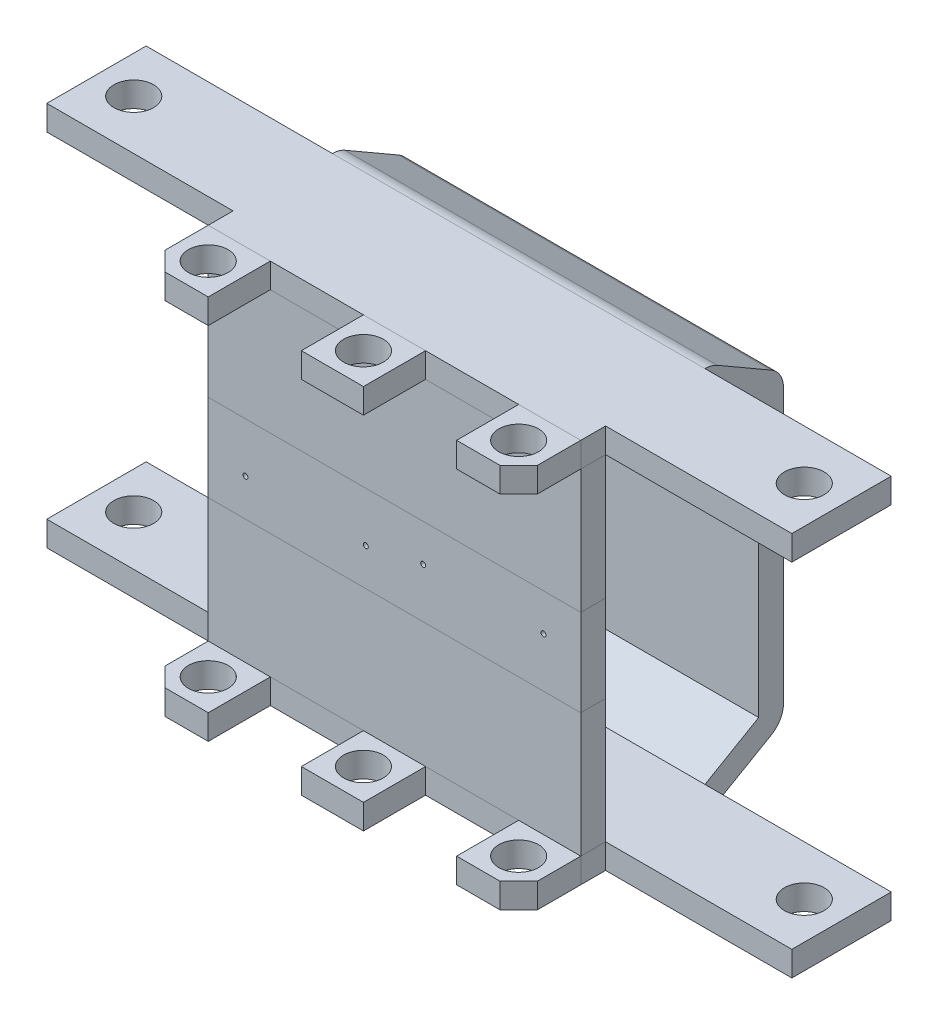
SolidWorks part; units mm, degrees
material "Mahogany"
ref_plane "Front Plane" through (0, 0, 0) normal (0, 0, 1) x (1, 0, 0)
ref_plane "Top Plane" through (0, 0, 0) normal (0, 1, 0) x (1, 0, 0)
ref_plane "Right Plane" through (0, 0, 0) normal (1, 0, 0) x (0, 0, -1)
sketch "Sketch1" plane through (0, 0, 0) normal (0, 0, 1) x (1, 0, 0)
  line L1 (0, 0) -> (-300, 0)
  line L2 (0, 0) -> (0, 200)
  line L3 (0, 200) -> (-300, 200)
  line L4 (-300, 0) -> (-300, 200)
  dimension "D1" = 300
  dimension "D2" = 200
extrude "Boss-Extrude1" add sketch "Sketch1" along normal blind 20
sketch "Sketch2" plane through (0, 0, 20) normal (0, 0, 1) x (1, 0, 0)
  line L0 (0, 200) -> (-300, 200) construction
  line L1 (-300, 200) -> (-300, 0) construction
  circle A0 centre (-270, 160) radius 2
  circle A1 centre (-173.0937, 160) radius 2
  dimension "D2" = 40
  dimension "D1" = 96.9063
  dimension "D3" = 40
  dimension "D4" = 30
extrude "Cut-Extrude1" cut sketch "Sketch2" against normal blind 20
sketch "Sketch3" plane through (0, 0, 0) normal (0, 0, -1) x (-1, 0, 0)
  line L0 (0, 0) -> (0, 200) construction
  line L1 (300, 0) -> (0, 0)
  line L2 (300, 0) -> (300, 130)
  line L3 (300, 130) -> (0, 130)
  line L4 (0, 0) -> (0, 130)
  dimension "D1" = 130
extrude "Cut-Extrude2" cut sketch "Sketch3" against normal blind 20
sketch "Sketch4" plane through (0, 0, 0) normal (0, 0, -1) x (-1, 0, 0)
  line L0 (0, 130) -> (0, 200) construction
  line L1 (0, 200) -> (300, 200) construction
  line L2 (300, 130) -> (0, 130) construction
  circle A0 centre (30, 170) radius 2
  circle A1 centre (126.9063, 170) radius 2
  dimension "D1" = 30
  dimension "D2" = 30
  dimension "D3" = 40
  dimension "D4" = 96.9063
extrude "Cut-Extrude3" cut sketch "Sketch4" against normal blind 20
sketch "Sketch5" plane through (0, 200, 0) normal (0, 1, 0) x (1, 0, 0)
  line L1 (0, -20) -> (-300, -20)
  line L2 (0, -20) -> (0, 0)
  line L3 (0, 0) -> (-300, 0)
  line L4 (-300, -20) -> (-300, 0)
extrude "Boss-Extrude2" add sketch "Sketch5" along normal blind 100 separate body
sketch "Sketch6" plane through (0, 130, 0) normal (0, -1, 0) x (1, 0, 0)
  line L1 (-300, 20) -> (0, 20)
  line L2 (-300, 20) -> (-300, 0)
  line L3 (-300, 0) -> (0, 0)
  line L4 (0, 20) -> (0, 0)
extrude "Boss-Extrude3" add sketch "Sketch6" along normal blind 100 separate body
sketch "Sketch9" plane through (0, 30, 0) normal (0, -1, 0) x (1, 0, 0)
  line L1 (-300, 20) -> (0, 20)
  line L2 (-300, 20) -> (-300, -80)
  line L3 (-300, -80) -> (0, -80)
  line L4 (0, 20) -> (0, -80)
  dimension "D1" = 100
extrude "Boss-Extrude6" add sketch "Sketch9" along normal blind 20 separate body
sketch "Sketch10" plane through (0, 300, 0) normal (0, 1, 0) x (1, 0, 0)
  line L1 (0, -20) -> (-300, -20)
  line L2 (0, -20) -> (0, 80)
  line L3 (0, 80) -> (-300, 80)
  line L4 (-300, -20) -> (-300, 80)
  dimension "D1" = 100
extrude "Boss-Extrude7" add sketch "Sketch10" along normal blind 20 separate body
sketch "Sketch14" plane through (0, 0, 0) normal (1, 0, 0) x (0, 0, -1)
  line L1 (80, 320) -> (0, 320)
  line L2 (80, 320) -> (80, 300)
  line L3 (80, 300) -> (0, 300)
  line L4 (0, 320) -> (0, 300)
extrude "Boss-Extrude11" add sketch "Sketch14" along normal blind 150 separate body
sketch "Sketch15" plane through (-300, 0, 0) normal (-1, 0, 0) x (0, 0, 1)
  line L1 (-80, 320) -> (0, 320)
  line L2 (-80, 320) -> (-80, 300)
  line L3 (-80, 300) -> (0, 300)
  line L4 (0, 320) -> (0, 300)
extrude "Boss-Extrude12" add sketch "Sketch15" along normal blind 150 separate body
sketch "Sketch16" plane through (-300, 0, 0) normal (-1, 0, 0) x (0, 0, 1)
  line L0 (20, 10) -> (-80, 10) construction
  line L1 (-80, 30) -> (0, 30)
  line L2 (-80, 30) -> (-80, 10)
  line L3 (-80, 10) -> (0, 10)
  line L4 (0, 30) -> (0, 10)
extrude "Boss-Extrude13" add sketch "Sketch16" along normal blind 150 separate body
sketch "Sketch17" plane through (0, 0, 0) normal (1, 0, 0) x (0, 0, -1)
  line L0 (80, 10) -> (-20, 10) construction
  line L1 (80, 30) -> (0, 30)
  line L2 (80, 30) -> (80, 10)
  line L3 (80, 10) -> (0, 10)
  line L4 (0, 30) -> (0, 10)
extrude "Boss-Extrude14" add sketch "Sketch17" along normal blind 150 separate body
sketch "Sketch18" plane through (0, 10, 0) normal (0, -1, 0) x (1, 0, 0)
  line L0 (150, 0) -> (150, -80) construction
  line L1 (150, -80) -> (0, -80) construction
  circle A0 centre (120, -40) radius 16
  dimension "D1" = 30
  dimension "D2" = 40
extrude "Cut-Extrude4" cut sketch "Sketch18" against normal blind 20
sketch "Sketch19" plane through (0, 300, 0) normal (0, -1, 0) x (1, 0, 0)
  line L0 (150, 0) -> (0, 0) construction
  line L1 (150, 0) -> (150, -80) construction
  circle A0 centre (120, -40) radius 16
  dimension "D1" = 40
  dimension "D2" = 30
extrude "Cut-Extrude5" cut sketch "Sketch19" against normal blind 20
sketch "Sketch20" plane through (0, 320, 0) normal (0, 1, 0) x (1, 0, 0)
  line L0 (-450, 0) -> (-300, 0) construction
  line L1 (-450, 0) -> (-450, 80) construction
  circle A0 centre (-420, 40) radius 16
  dimension "D1" = 40
  dimension "D2" = 30
extrude "Cut-Extrude6" cut sketch "Sketch20" against normal blind 20
sketch "Sketch21" plane through (0, 30, 0) normal (0, 1, 0) x (1, 0, 0)
  line L0 (-450, 0) -> (-450, 80) construction
  line L1 (-450, 80) -> (-300, 80) construction
  circle A0 centre (-420, 40) radius 16
  dimension "D1" = 30
  dimension "D2" = 40
extrude "Cut-Extrude7" cut sketch "Sketch21" against normal blind 20
sketch "Sketch22" plane through (0, 0, 20) normal (0, 0, 1) x (1, 0, 0)
  line L0 (-300, 300) -> (0, 300) construction
  line L1 (-300, 320) -> (-250, 320)
  line L2 (-300, 320) -> (-300, 300)
  line L3 (-300, 300) -> (-250, 300)
  line L4 (-250, 320) -> (-250, 300)
  line L5 (-300, 320) -> (0, 320) construction
  line L6 (-175, 320) -> (-125, 320)
  line L7 (-175, 320) -> (-175, 300)
  line L8 (-175, 300) -> (-125, 300)
  line L9 (-125, 320) -> (-125, 300)
  line L11 (0, 320) -> (-50, 320)
  line L12 (0, 320) -> (0, 300)
  line L13 (0, 300) -> (-50, 300)
  line L14 (-50, 320) -> (-50, 300)
  point P18 (-175, 310)
  dimension "D1" = 50
  dimension "D2" = 50
  dimension "D3" = 50
  dimension "D4" = 75
  dimension "D5" = 75
extrude "Boss-Extrude15" add sketch "Sketch22" along normal blind 50 separate body
sketch "Sketch23" plane through (0, 0, 20) normal (0, 0, 1) x (1, 0, 0)
  line L0 (0, 10) -> (-300, 10) construction
  line L1 (-300, 30) -> (-250, 30)
  line L2 (-300, 30) -> (-300, 10)
  line L3 (-300, 10) -> (-250, 10)
  line L4 (-250, 30) -> (-250, 10)
  line L5 (0, 30) -> (-300, 30) construction
  line L6 (-175, 30) -> (-125, 30)
  line L7 (-175, 30) -> (-175, 10)
  line L8 (-175, 10) -> (-125, 10)
  line L9 (-125, 30) -> (-125, 10)
  line L10 (0, 30) -> (-300, 30) construction
  line L11 (0, 10) -> (-50, 10)
  line L12 (0, 10) -> (0, 30)
  line L13 (0, 30) -> (-50, 30)
  line L14 (-50, 10) -> (-50, 30)
  dimension "D1" = 50
  dimension "D2" = 50
  dimension "D3" = 50
  dimension "D4" = 75
extrude "Boss-Extrude16" add sketch "Sketch23" along normal blind 50 separate body
sketch "Sketch24" plane through (0, 10, 0) normal (0, -1, 0) x (1, 0, 0)
  line L1 (-50, 70) -> (-50, 20) construction
  line L2 (-50, 70) -> (0, 70) construction
  line L3 (0, 55) -> (-15, 70)
  line L4 (0, 70) -> (0, 20) construction
  line L5 (0, 70) -> (0, 55)
  line L6 (-15, 70) -> (0, 70)
  circle A0 centre (-25, 45) radius 16
  dimension "D1" = 25
  dimension "D2" = 25
  dimension "D3" = 15
  dimension "D4" = 15
extrude "Cut-Extrude8" cut sketch "Sketch24" against normal blind 20
sketch "Sketch25" plane through (0, 10, 0) normal (0, -1, 0) x (1, 0, 0)
  line L0 (-125, 70) -> (-125, 20) construction
  line L1 (-175, 70) -> (-125, 70) construction
  circle A0 centre (-150, 45) radius 16
  dimension "D1" = 25
  dimension "D2" = 25
extrude "Cut-Extrude9" cut sketch "Sketch25" against normal blind 20
sketch "Sketch26" plane through (0, 10, 0) normal (0, -1, 0) x (1, 0, 0)
  line L0 (-300, 70) -> (-250, 70) construction
  line L1 (-300, 70) -> (-300, 20) construction
  line L2 (-300, 55) -> (-285, 70)
  line L3 (-285, 70) -> (-300, 70)
  line L4 (-300, 70) -> (-300, 55)
  circle A0 centre (-275, 45) radius 16
  dimension "D1" = 25
  dimension "D2" = 25
  dimension "D3" = 15
  dimension "D4" = 15
extrude "Cut-Extrude10" cut sketch "Sketch26" against normal blind 20
sketch "Sketch27" plane through (0, 320, 0) normal (0, 1, 0) x (1, 0, 0)
  line L0 (-300, -70) -> (-300, -20) construction
  line L1 (-250, -70) -> (-300, -70) construction
  line L2 (-300, -55) -> (-285, -70)
  line L3 (-285, -70) -> (-300, -70)
  line L4 (-300, -70) -> (-300, -55)
  circle A0 centre (-275, -45) radius 16
  dimension "D1" = 25
  dimension "D2" = 25
  dimension "D3" = 15
  dimension "D4" = 15
extrude "Cut-Extrude11" cut sketch "Sketch27" against normal blind 20
sketch "Sketch28" plane through (0, 320, 0) normal (0, 1, 0) x (1, 0, 0)
  line L0 (-175, -70) -> (-175, -20) construction
  line L1 (-125, -70) -> (-175, -70) construction
  circle A0 centre (-150, -45) radius 16
  dimension "D1" = 25
  dimension "D2" = 25
extrude "Cut-Extrude12" cut sketch "Sketch28" against normal blind 20
sketch "Sketch29" plane through (0, 320, 0) normal (0, 1, 0) x (1, 0, 0)
  line L0 (-50, -70) -> (-50, -20) construction
  line L1 (0, -70) -> (-50, -70) construction
  line L2 (0, -55) -> (-15, -70)
  line L3 (0, -70) -> (0, -20) construction
  line L4 (-15, -70) -> (0, -70)
  line L5 (0, -70) -> (0, -55)
  circle A0 centre (-25, -45) radius 16
  dimension "D1" = 25
  dimension "D2" = 25
  dimension "D3" = 15
  dimension "D4" = 15
extrude "Cut-Extrude13" cut sketch "Sketch29" against normal blind 20
sketch "Sketch30" plane through (0, 0, -80) normal (0, 0, -1) x (-1, 0, 0)
  line L1 (0, 30) -> (300, 30)
  line L2 (0, 30) -> (0, 10)
  line L3 (0, 10) -> (300, 10)
  line L4 (300, 30) -> (300, 10)
revolve "Revolve1" add sketch "Sketch30" angle 30 about L1
sketch "Sketch31" plane through (0, 0, -80) normal (0, 0, -1) x (-1, 0, 0)
  line L1 (0, 320) -> (300, 320)
  line L2 (0, 320) -> (0, 300)
  line L3 (0, 300) -> (300, 300)
  line L4 (300, 320) -> (300, 300)
revolve "Revolve2" add sketch "Sketch31" angle 30 about L3
sketch "Sketch33" plane through (0, 42.141, -72.9904) normal (0, 0.5, -0.866) x (-1, 0, 0)
  line L1 (0, -34.0192) -> (300, -34.0192)
  line L2 (0, -34.0192) -> (0, -14.0192)
  line L3 (0, -14.0192) -> (300, -14.0192)
  line L4 (300, -34.0192) -> (300, -14.0192)
extrude "Boss-Extrude18" add sketch "Sketch33" along normal blind 50
sketch "Sketch34" plane through (0, 40.359, 69.9038) normal (0, -0.5, -0.866) x (-1, 0, 0)
  line L1 (0, 319.8076) -> (300, 319.8076)
  line L2 (0, 319.8076) -> (0, 299.8076)
  line L3 (0, 299.8076) -> (300, 299.8076)
  line L4 (300, 319.8076) -> (300, 299.8076)
extrude "Boss-Extrude19" add sketch "Sketch34" along normal blind 50
sketch "Sketch35" plane through (0, 67.141, -116.2917) normal (0, 0.5, -0.866) x (-1, 0, 0)
  line L1 (0, -34.0192) -> (300, -34.0192)
  line L2 (0, -34.0192) -> (0, -14.0192)
  line L3 (0, -14.0192) -> (300, -14.0192)
  line L4 (300, -34.0192) -> (300, -14.0192)
revolve "Revolve3" add sketch "Sketch35" angle 60 about L3
sketch "Sketch36" plane through (0, 15.359, 26.6025) normal (0, -0.5, -0.866) x (-1, 0, 0)
  line L1 (0, 319.8076) -> (300, 319.8076)
  line L2 (0, 319.8076) -> (0, 299.8076)
  line L3 (0, 299.8076) -> (300, 299.8076)
  line L4 (300, 319.8076) -> (300, 299.8076)
revolve "Revolve4" add sketch "Sketch36" angle 60 about L3
sketch "Sketch37" plane through (0, 55, 0) normal (0, 1, 0) x (1, 0, 0)
  line L1 (0, 143.3013) -> (-300, 143.3013)
  line L2 (0, 143.3013) -> (0, 123.3013)
  line L3 (0, 123.3013) -> (-300, 123.3013)
  line L4 (-300, 143.3013) -> (-300, 123.3013)
extrude "Boss-Extrude20" add sketch "Sketch37" along normal blind 220
sketch "Sketch38" plane through (0, 0, -143.3013) normal (0, 0, -1) x (-1, 0, 0)
  line L0 (0, 55) -> (300, 55) construction
  line L1 (105, 150) -> (235, 150)
  line L2 (105, 150) -> (105, 180)
  line L3 (105, 180) -> (235, 180)
  line L4 (235, 150) -> (235, 180)
  line L5 (0, 275) -> (0, 55) construction
  dimension "D1" = 130
  dimension "D2" = 30
  dimension "D3" = 95
  dimension "D4" = 105
extrude "Boss-Extrude21" add sketch "Sketch38" along normal blind 1
